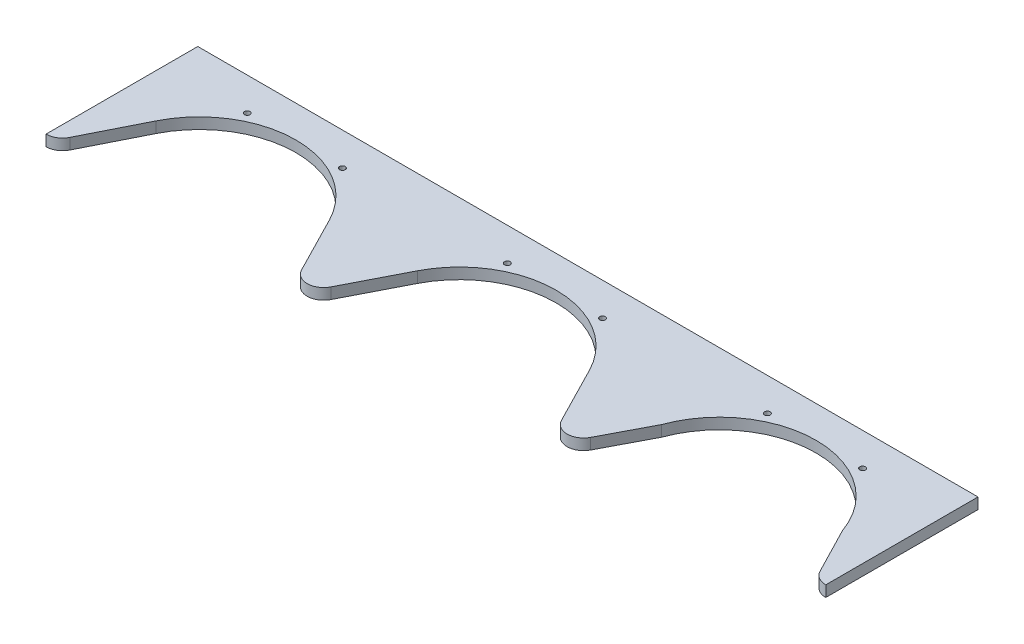
SolidWorks part; units mm, degrees
ref_plane "Front Plane" through (0, 0, 0) normal (0, 0, 1) x (1, 0, 0)
ref_plane "Top Plane" through (0, 0, 0) normal (0, 1, 0) x (1, 0, 0)
ref_plane "Right Plane" through (0, 0, 0) normal (1, 0, 0) x (0, 0, -1)
sketch "Sketch1" plane through (0, 0, 0) normal (0, 1, 0) x (1, 0, 0)
  line L0 (-129.7899, -67.5734) -> (-129.7899, 62.6016)
  line L1 (-280.0732, 62.6016) -> (170.7768, 62.6016)
  line L2 (-280.0732, 62.6016) -> (-280.0732, -25.1078)
  line L3 (-280.0732, -67.5734) -> (177.1268, -67.5734)
  line L4 (170.7768, 62.6016) -> (170.7768, -25.3728)
  line L5 (20.4934, -67.5734) -> (20.4934, 62.6016)
  line L6 (-155.1955, 13.7801) -> (-129.7899, -35.8234)
  line L7 (-129.7899, -35.8234) -> (-104.3843, 13.7801)
  line L8 (-4.9122, 13.7801) -> (20.4934, -35.8234)
  line L9 (20.4934, -35.8234) -> (50.0821, 20.6717)
  line L10 (-254.8688, 13.3835) -> (-271.5612, -19.8573)
  line L11 (141.188, 20.6717) -> (162.3144, -20.2198)
  circle A0 centre (-204.9316, -11.6934) radius 55.88
  circle A1 centre (-54.6482, -11.6934) radius 55.88
  circle A2 centre (95.6351, -11.6934) radius 55.88
  circle A3 centre (-280.0732, -15.5828) radius 9.525
  circle A4 centre (170.7768, -15.8478) radius 9.525
  circle A9 centre (-232.4398, 43.5516) radius 1.6383
  circle A10 centre (-177.4234, 43.5516) radius 1.6383
  circle A11 centre (-82.1564, 43.5516) radius 1.6383
  circle A12 centre (-27.14, 43.5516) radius 1.6383
  circle A13 centre (68.1269, 43.5516) radius 1.6383
  circle A14 centre (123.1433, 43.5516) radius 1.6383
  dimension "D3" = 111.76
  dimension "D4" = 111.76
  dimension "D5" = 111.76
  dimension "D15" = 3.2766
  dimension "D16" = 3.2766
  dimension "D17" = 3.2766
  dimension "D18" = 3.2766
  dimension "D19" = 3.2766
  dimension "D20" = 3.2766
  dimension "D24" = 19.05
  dimension "D25" = 19.05
  dimension "D1" = 450.85
  dimension "D2" = 130.175
  dimension "D6" = 150.2833
  dimension "D7" = 150.2833
  dimension "D8" = 75.1417
  dimension "D9" = 75.1417
  dimension "D10" = 75.1417
  dimension "D11" = 55.0164
  dimension "D12" = 27.5082
  dimension "D13" = 55.0164
  dimension "D14" = 27.5082
  dimension "D21" = 19.05
  dimension "D22" = 55.0164
  dimension "D23" = 27.5082
  dimension "D29" = 31.75
  dimension "D30" = 31.75
extrude "Boss-Extrude1" add sketch "Sketch1" against normal blind 6.35 contours A3 L10 A0 L6 L0 L1 L2 A10 A9 | L2 A3 | A1 L8 L5 L1 L0 L7 A12 A11 | A4 L4 L1 L5 L9 A2 L11 A14 A13 | L4 A4
fillet "Fillet3" radius 9.525 2 edges at (20.4934, -3.175, 35.8234) (-129.7899, -3.175, 35.8234)
